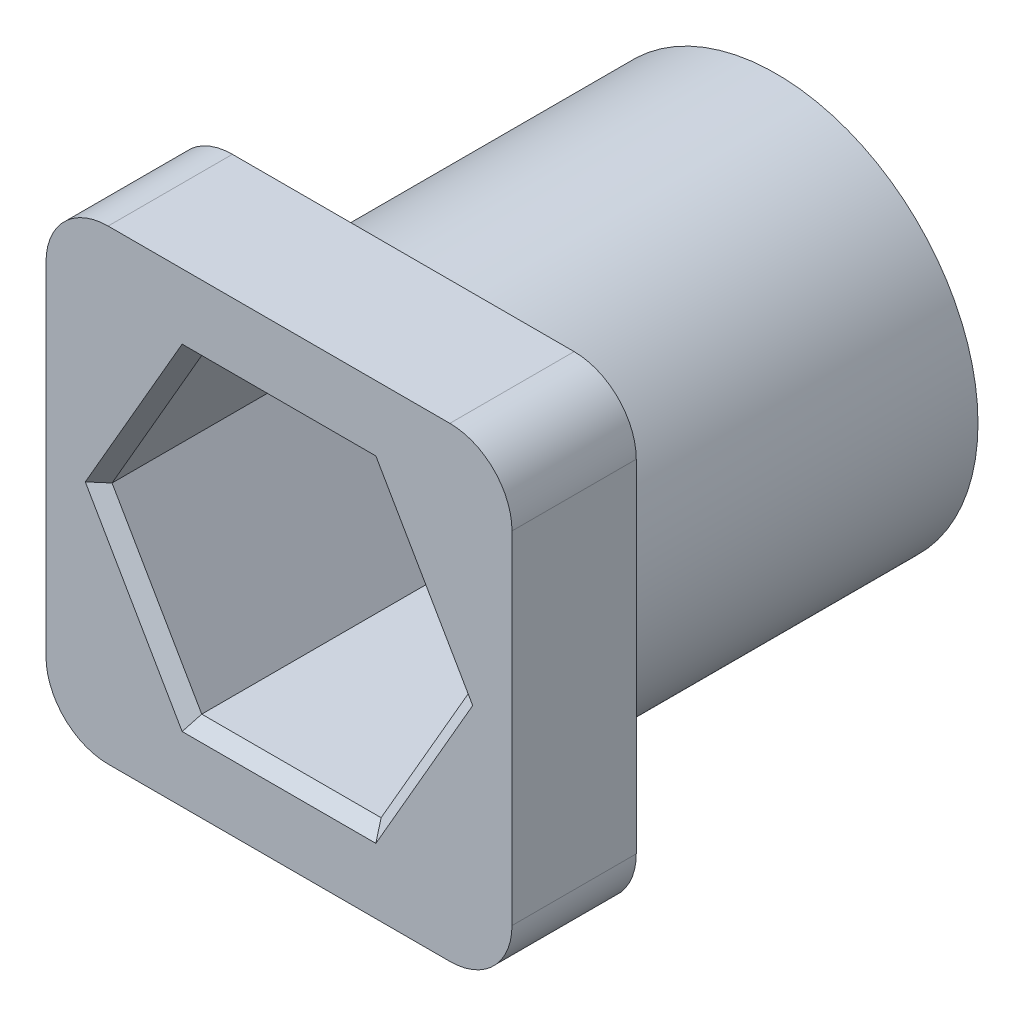
SolidWorks part; units mm, degrees
ref_plane "Front Plane" through (0, 0, 0) normal (0, 0, 1) x (1, 0, 0)
ref_plane "Top Plane" through (0, 0, 0) normal (0, 1, 0) x (1, 0, 0)
ref_plane "Right Plane" through (0, 0, 0) normal (1, 0, 0) x (0, 0, -1)
sketch "Sketch1" plane through (0, 0, 0) normal (0, 0, 1) x (1, 0, 0)
  line L1 (-9.525, -9.525) -> (9.525, -9.525)
  line L2 (-9.525, -9.525) -> (-9.525, 9.525)
  line L3 (-9.525, 9.525) -> (9.525, 9.525)
  line L4 (9.525, -9.525) -> (9.525, 9.525)
  line L5 (-9.525, -9.525) -> (9.525, 9.525) construction
  line L6 (-9.525, 9.525) -> (9.525, -9.525) construction
  point P0 (0, 0)
  dimension "D1" = 19.05
extrude "Boss-Extrude1" add sketch "Sketch1" against normal blind 5.08
sketch "Sketch2" plane through (0, 0, -5.08) normal (0, 0, -1) x (-1, 0, 0)
  circle A0 centre (0, 0) radius 8.255
  dimension "D1" = 16.51
extrude "Boss-Extrude2" add sketch "Sketch2" along normal blind 15.24
sketch "Sketch3" plane through (0, 0, 0) normal (0, 0, 1) x (1, 0, 0)
  line L0 (0, 0) -> (0, 9.525) construction
  line L1 (3.6662, 6.35) -> (-3.6662, 6.35)
  line L2 (-3.6662, 6.35) -> (-7.3323, 0)
  line L3 (-7.3323, 0) -> (-3.6662, -6.35)
  line L4 (-3.6662, -6.35) -> (3.6662, -6.35)
  line L5 (3.6662, -6.35) -> (7.3323, 0)
  line L6 (7.3323, 0) -> (3.6662, 6.35)
  line L7 (9.525, 9.525) -> (-9.525, 9.525) construction
  circle A0 centre (0, 0) radius 6.35 construction
  point P1 (0, 6.35)
  dimension "D1" = 12.7
extrude "Cut-Extrude1" cut sketch "Sketch3" against normal through all
fillet "Fillet1" radius 2.54 4 edges at (9.525, -9.525, -2.54) (-9.525, -9.525, -2.54) (9.525, 9.525, -2.54) (-9.525, 9.525, -2.54)
chamfer "Chamfer1" distance 0.508 angle 45 6 edges at (5.4993, 3.175, 0) (5.4993, -3.175, 0) (0, -6.35, 0) (-5.4993, -3.175, 0) (-5.4993, 3.175, 0) (0, 6.35, 0)
